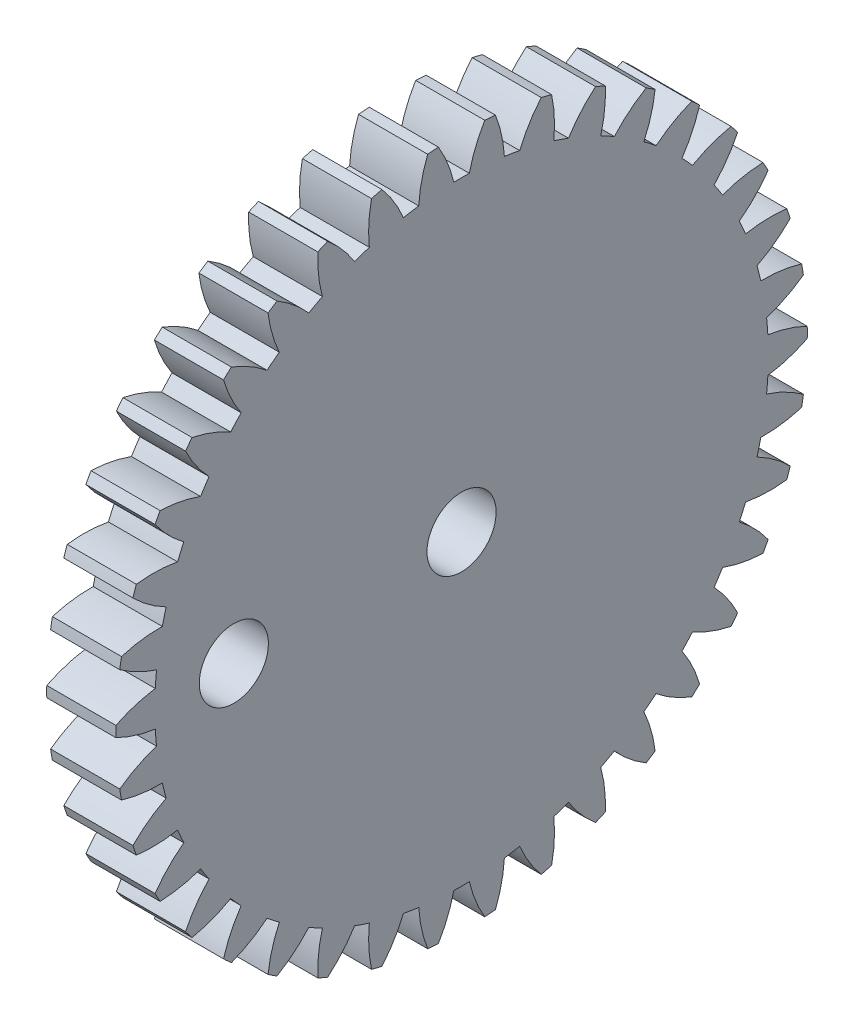
SolidWorks part; units mm, degrees
ref_plane "Plane1" through (0, 0, 0) normal (0, 0, 1) x (1, 0, 0)
ref_plane "Plane2" through (0, 0, 0) normal (0, 1, 0) x (1, 0, 0)
ref_plane "Plane3" through (0, 0, 0) normal (1, 0, 0) x (0, 0, -1)
other "Configuration Table"
sketch "HoldingSke" plane through (0, 0, 0) normal (0, 1, 0) x (1, 0, 0)
  line L0 (0, 0) -> (320.2476, -250.2048)
  line L1 (-15, 0) -> (100, 0) construction
  line L2 (0, 0) -> (-2.1039, 2.3779)
  line L3 (0, 0) -> (-11.863, 4.5341)
  line L4 (0, 0) -> (6.8053, 5.3169)
  line L5 (0, 0) -> (-47.5972, -17.7524)
  line L6 (0, 0) -> (-5.2639, -3.5516)
  line L7 (-2.1039, 2.3779) -> (8.8308, 51.9871)
  line L8 (-76.2, 54.61) -> (-69.596, 54.61)
  line L9 (-71.009, 38.7566) -> (-53.1078, 45.2721)
  line L10 (-76.2, 71.12) -> (104.1128, 71.12)
  line L11 (0, 0) -> (-6.35, 0)
  line L12 (-76.2, 101.6) -> (-76.1428, 101.6)
  line L13 (24.9733, 27.94) -> (52.9518, 28.4284)
  line L14 (24.9733, 27.94) -> (24.9746, 27.94)
  line L15 (24.9733, 27.94) -> (100.4006, 29.5858)
  circle A0 centre (0, 0) radius 3.175
  circle A1 centre (0, 0) radius 28.1769
  circle A2 centre (0, 0) radius 38.1
  circle A3 centre (0, 0) radius 3.175
  dimension "MHD" = 56.3537
  dimension "Hub_dia" = 76.2
  dimension "Bore" = 6.35
  dimension "MBD" = 6.35
  dimension "Num_teeth" = 38
  dimension "Pitch" = 406.4
  dimension "Overall_len" = 50.8
  dimension "Show_teeth" = 38
  dimension "Thickness" = 6.35
  dimension "OAL" = 50.8001
  dimension "T_dim" = 6.604
  dimension "Ap" = 20
  dimension "H" = 19.05
  dimension "Pitch_radius" = 180.3128
  dimension "Width" = 6.35
  dimension "Backlash" = 0.0571
  dimension "Addendum_fac" = 1
  dimension "Dedendum_fac" = 1.25
  dimension "Clearance_fac" = 0.25
  dimension "Dedendum_add" = 0.0013
sketch "BasProSke" plane through (0, 0, 0) normal (0, 1, 0) x (1, 0, 0)
  line L0 (-10, 0) -> (60, 0) construction
  line L1 (0, 0) -> (0, 31.75)
  line L2 (0, 0) -> (6.35, 0)
  line L3 (6.35, 0) -> (6.35, 31.75)
  line L4 (6.35, 31.75) -> (0, 31.75)
  dimension "Thickness" = 6.35
  dimension "Diameter" = 63.5
revolve "Base-Revolve" add sketch "BasProSke" angle 360 about L0
sketch "TooCutSke" plane through (0, 0, 0) normal (1, 0, 0) x (0, 0, -1)
  line L1 (0, 0) -> (0, 107) construction
  line L2 (0, 0) -> (-1.3465, 30.1324) construction
  line L3 (0, 0) -> (-4.978, 60.0755) construction
  line L4 (-1.3465, 30.1324) -> (-2.489, 30.0378) construction
  arc A0 (0.7117, 28.1679) -> (-0.7117, 28.1679) centre (0, 0) ccw
  arc A1 (2.1467, 31.7028) -> (-2.1467, 31.7028) centre (0, 0) ccw
  circle A2 centre (0, 0) radius 30.1625 construction
  circle A3 centre (0, 0) radius 28.3435 construction
  arc A4 (-0.7117, 28.1679) -> (-2.1467, 31.7028) centre (-12.4675, 25.4541) ccw
  arc A5 (2.1467, 31.7028) -> (0.7117, 28.1679) centre (12.4675, 25.4541) ccw
  dimension "Root_dia" = 56.3537
  dimension "Overcut_dia" = 63.5508
  dimension "Pitch_dia" = 60.325
  dimension "Base_dia" = 56.687
  dimension "Flank_rad" = 12.065
  dimension "Half_ang" = 4.737
  dimension "Half_CT" = 1.1465
extrude "ToothCut" cut sketch "TooCutSke" along normal through all
fillet "Breaks" [suppressed] radius 0.0318
fillet "RootFillets" [suppressed] radius 0.3981
pattern_circular "TeethCuts" count 38 every 9.474 about axis through (-10, 0, 0) along (1, 0, 0) of "ToothCut", "RootFillets", "Breaks"
sketch "HubNeaOneSke" plane through (0, 0, 0) normal (-1, 0, 0) x (0, 0, 1)
  circle A0 centre (0, 0) radius 28.1769
  dimension "Diameter" = 56.3537
extrude "HubNearOne" [suppressed] add sketch "HubNeaOneSke" along normal blind 44.4501
sketch "HubNeaBotSke" plane through (0, 0, 0) normal (-1, 0, 0) x (0, 0, 1)
  circle A0 centre (0, 0) radius 28.1769
  dimension "Diameter" = 56.3537
extrude "HubNearBoth" [suppressed] add sketch "HubNeaBotSke" along normal blind 22.225
ref_plane "FarPln" through (6.35, 0, 0) normal (1, 0, 0) x (0, 0, -1)
sketch "HubFarSke" plane through (6.35, 0, 0) normal (1, 0, 0) x (0, 0, -1)
  circle A0 centre (0, 0) radius 28.1769
  dimension "Diameter" = 56.3537
extrude "HubFar" [suppressed] add sketch "HubFarSke" along normal blind 22.225
sketch "BorSke" plane through (0, 0, 0) normal (1, 0, 0) x (0, 0, -1)
  circle A0 centre (0, 0) radius 3.175
  dimension "Diameter" = 6.35
extrude "Bore" cut sketch "BorSke" along normal mid plane 101.6001
sketch "KeySke" plane through (0, 0, 0) normal (1, 0, 0) x (0, 0, -1)
  line L0 (-0.127, 0) -> (-0.127, 3.429)
  line L1 (-0.127, 3.429) -> (0.127, 3.429)
  line L2 (0.127, 3.429) -> (0.127, 0)
  line L3 (0, 0) -> (0, 34) construction
  line L4 (-0.127, 0) -> (0.127, 0)
  dimension "Offset" = 3.429
  dimension "Width" = 0.254
extrude "Keyway" [suppressed] cut sketch "KeySke" along normal mid plane 101.6001
pattern_circular "Keyway2" [suppressed] count 2 every 90 about axis through (-10, 0, 0) along (1, 0, 0)
sketch "Sketch1" plane through (6.35, 0, 0) normal (1, 0, 0) x (0, 0, -1)
  line L0 (0, 0) -> (-20.914, 0) construction
  circle A0 centre (-20.914, 0) radius 3.175
  dimension "D2" = 6.35
  dimension "D1" = 20.914
extrude "Cut-Extrude1" cut sketch "Sketch1" against normal up to surface (6.35 mm away) up to face at (0, 0, -3.175)
equation "' \"Pitch@HoldingSke\" = 4"
equation "' \"Num_teeth@HoldingSke\" = 12"
equation "' \"Ap@HoldingSke\" =  20"
equation "' \"Ap@HoldingSke\" = 20"
equation "' \"Width@HoldingSke\" = 0.5"
equation "' \"Hub_dia@HoldingSke\"= 1"
equation "' \"Hub_dia@HoldingSke\" = 1"
equation "' \"Overall_len@HoldingSke\" = 1.0"
equation "' \"Bore@HoldingSke\" = 0.75"
equation "' \"T_dim@HoldingSke\" = 0.85"
equation "' \"Width@KeySke\" = 0.25"
equation "' \"Show_teeth@HoldingSke\" = 13"
equation "' \"Backlash@HoldingSke\" = 0.009"
equation "' \"Addendum_fac@HoldingSke\" = 1.0"
equation "' \"Dedendum_fac@HoldingSke\" = 1.25"
equation "' \"Dedendum_add@HoldingSke\" = 0.00005"
equation "' \"Clearance_fac@HoldingSke\" = 0.25"
equation "' \"Pitch@HoldingSke\" = 0.5"
equation "' \"Num_teeth@HoldingSke\" = 23"
equation "' \"Show_teeth@HoldingSke\" = 23"
equation "' \"Backlash@HoldingSke\" = 0.0375"
equation "\"Overcut_dia@TooCutSke\" = (\"Num_teeth@HoldingSke\" + 2 * \"Addendum_fac@HoldingSke\") / \"Pitch@HoldingSke\" + 0.002"
equation "\"Pitch_dia@TooCutSke\" = \"Num_teeth@HoldingSke\" / \"Pitch@HoldingSke\""
equation "\"Base_dia@TooCutSke\" = \"Num_teeth@HoldingSke\" / \"Pitch@HoldingSke\" * cos((\"Ap@HoldingSke\"  * 3.14159265 / 180))"
equation "\"Root_dia@TooCutSke\" = (\"Num_teeth@HoldingSke\" + 2) / \"Pitch@HoldingSke\" - 2 * (\"Addendum_fac@HoldingSke\" + \"Dedendum_fac@HoldingSke\") / \"Pitch@HoldingSke\" - \"Dedendum_add@HoldingSke\" * 2"
equation "\"Half_ang@TooCutSke\" = 180 / \"Num_teeth@HoldingSke\""
equation "\"Half_CT@TooCutSke\" = \"Num_teeth@HoldingSke\" / \"Pitch@HoldingSke\" * sin((3.14159265 / 2 / \"Num_teeth@HoldingSke\")) / 2 - 7 * \"Backlash@HoldingSke\" / 4"
equation "\"Flank_rad@TooCutSke\" = \"Num_teeth@HoldingSke\" / \"Pitch@HoldingSke\" / 5"
equation "\"Radius@RootFillets\" = \"Clearance_fac@HoldingSke\" / \"Pitch@HoldingSke\" + \"Dedendum_add@HoldingSke\""
equation "\"Break_rad@Breaks\" = 0.02 / \"Pitch@HoldingSke\""
equation "\"Thickness@HoldingSke\" = \"Width@HoldingSke\""
equation "\"OAL@HoldingSke\" = \"Thickness@HoldingSke\""
equation "\"MHD@HoldingSke\" = (\"Num_teeth@HoldingSke\" + 2) / \"Pitch@HoldingSke\" - 2 * (\"Addendum_fac@HoldingSke\" + \"Dedendum_fac@HoldingSke\")  / \"Pitch@HoldingSke\" - \"Dedendum_add@HoldingSke\" * 2"
equation "\"MBD@HoldingSke\" = (\"Num_teeth@HoldingSke\" + 2) / \"Pitch@HoldingSke\" - 2 * (\"Addendum_fac@HoldingSke\" + \"Dedendum_fac@HoldingSke\")  / \"Pitch@HoldingSke\" - \"Dedendum_add@HoldingSke\" * 2 - 0.002"
equation "\"MHD@HoldingSke\" = ((sgn( \"MHD@HoldingSke\" - \"Hub_dia@HoldingSke\" )-1)*( \"MHD@HoldingSke\" - \"Hub_dia@HoldingSke\" ))/-2+ \"Hub_dia@HoldingSke\""
equation "\"MBD@HoldingSke\" = ((sgn( \"MBD@HoldingSke\" - \"Bore@HoldingSke\" )-1)*( \"MBD@HoldingSke\" - \"Bore@HoldingSke\" ))/-2+ \"Bore@HoldingSke\""
equation "\"OAL@HoldingSke\" = ((sgn( \"OAL@HoldingSke\" - \"Overall_len@HoldingSke\" )+1)*( \"OAL@HoldingSke\" - \"Overall_len@HoldingSke\" ))/2 + \"Overall_len@HoldingSke\" + 0.000002"
equation "\"Num_teeth@TeethCuts\" = int( \"Show_teeth@HoldingSke\" ) + 1"
equation "\"Num_teeth@TeethCuts\" = ((sgn( \"Num_teeth@TeethCuts\" - \"Num_teeth@HoldingSke\" )-1)*( \"Num_teeth@TeethCuts\" - \"Num_teeth@HoldingSke\" ))/-2+ \"Num_teeth@HoldingSke\""
equation "\"Num_teeth@TeethCuts\" = ((sgn( \"Num_teeth@TeethCuts\" - 2.0)+1)*( \"Num_teeth@TeethCuts\" - 2.0))/2 +2.0"
equation "\"Angle@TeethCuts\" = 360.0 / \"Num_teeth@HoldingSke\""
equation "\"Diameter@BasProSke\" = (\"Num_teeth@HoldingSke\" + 2 * \"Addendum_fac@HoldingSke\") / \"Pitch@HoldingSke\""
equation "\"Thickness@BasProSke\"  = \"Thickness@HoldingSke\""
equation "' \"Fillet_rad@BasProSke\" =  \"Thickness@HoldingSke\" * 0.05"
equation "' \"Fillet_rad@BasProSke\" = \"Thickness@HoldingSke\" * 0.05"
equation "\"MHD@HoldingSke\" = ((sgn( \"MHD@HoldingSke\" - \"Root_dia@TooCutSke\" )-1)*( \"MHD@HoldingSke\" - \"Root_dia@TooCutSke\" ))/-2+ \"Root_dia@TooCutSke\""
equation "\"Diameter@HubNeaOneSke\" = \"MHD@HoldingSke\""
equation "\"Length@HubNearOne\" = \"OAL@HoldingSke\" - \"Thickness@BasProSke\""
equation "\"Diameter@HubNeaBotSke\" = \"MHD@HoldingSke\""
equation "\"Length@HubNearBoth\" = ( \"OAL@HoldingSke\" - \"Thickness@BasProSke\" ) / 2.0"
equation "\"Thickness@FarPln\" = \"Thickness@BasProSke\""
equation "\"Diameter@HubFarSke\" = \"MHD@HoldingSke\""
equation "\"Length@HubFar\" = ( \"OAL@HoldingSke\" - \"Thickness@BasProSke\" ) / 2.0"
equation "\"Diameter@BorSke\" = \"MBD@HoldingSke\""
equation "\"D1@Bore\" = \"OAL@HoldingSke\" * 2.0"
equation "\"D1@Keyway\" = \"OAL@HoldingSke\" * 2.0"
equation "\"Offset@KeySke\" = \"T_dim@HoldingSke\" - \"MBD@HoldingSke\" / 2.0"
